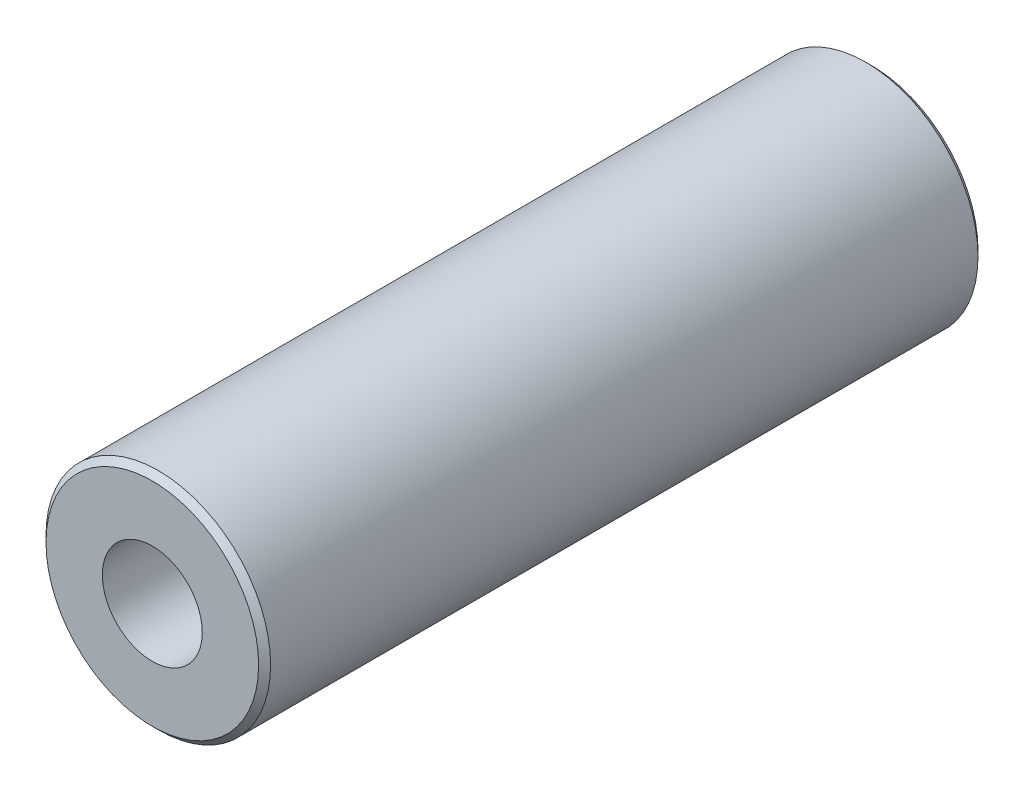
SolidWorks part; units mm, degrees
material "Alloy Steel"
ref_plane "Front Plane" through (0, 0, 0) normal (0, 0, 1) x (1, 0, 0)
ref_plane "Top Plane" through (0, 0, 0) normal (0, 1, 0) x (1, 0, 0)
ref_plane "Right Plane" through (0, 0, 0) normal (1, 0, 0) x (0, 0, -1)
sketch "Base Sketch" plane through (0, 0, 0) normal (0, 0, 1) x (1, 0, 0)
  circle A0 centre (0, 0) radius 7.1374
  circle A1 centre (0, 0) radius 3.175
  dimension "D1" = 14.2748
  dimension "D2" = 6.35
extrude "Base Extrude" add sketch "Base Sketch" against normal blind 45.72
chamfer "End Chamfer" distance 0.381 angle 45 2 edges at (7.1374, 0, 0) (7.1374, 0, -45.72)
